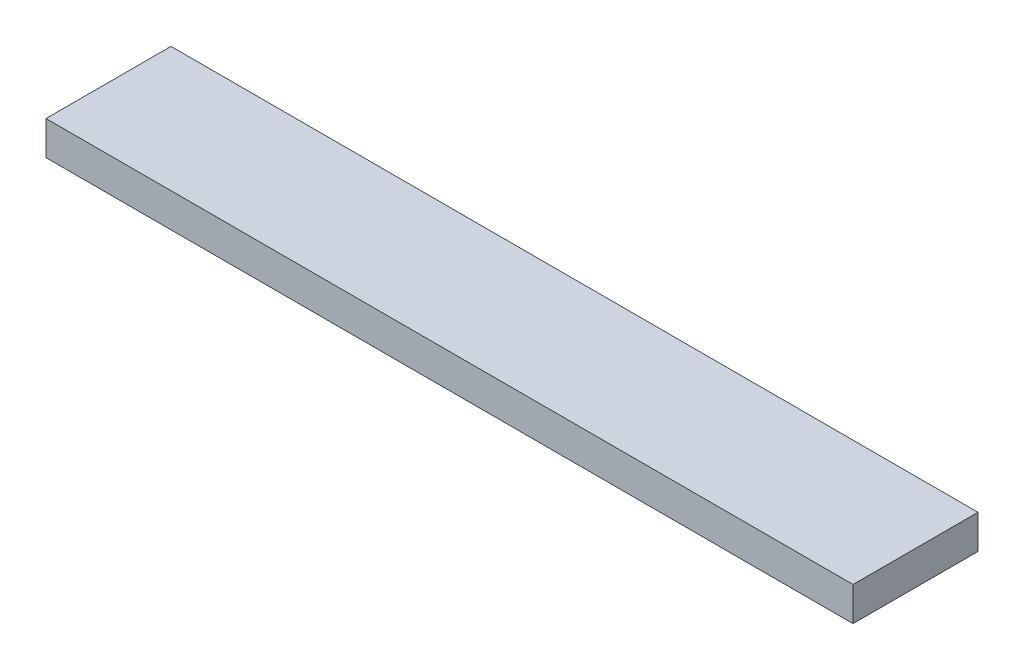
SolidWorks part; units mm, degrees
ref_plane "前视基准面" through (0, 0, 0) normal (0, 0, 1) x (1, 0, 0)
ref_plane "上视基准面" through (0, 0, 0) normal (0, 1, 0) x (1, 0, 0)
ref_plane "右视基准面" through (0, 0, 0) normal (1, 0, 0) x (0, 0, -1)
sketch "草图1" plane through (0, 0, 0) normal (0, 1, 0) x (1, 0, 0)
  line L1 (0, 0) -> (226, 0)
  line L2 (0, 0) -> (0, -35)
  line L3 (0, -35) -> (226, -35)
  line L4 (226, 0) -> (226, -35)
  dimension "D1" = 226
  dimension "D2" = 35
extrude "凸台-拉伸1" add sketch "草图1" along normal blind 9.5
